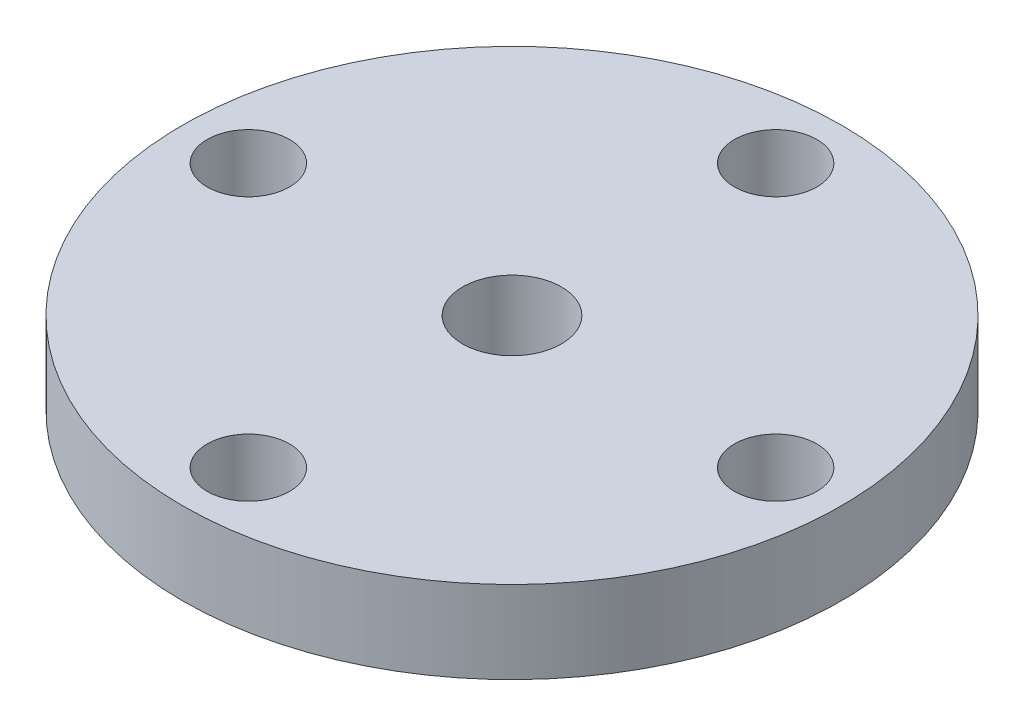
SolidWorks part; units mm, degrees
ref_plane "Front Plane" through (0, 0, 0) normal (0, 0, 1) x (1, 0, 0)
ref_plane "Top Plane" through (0, 0, 0) normal (0, 1, 0) x (1, 0, 0)
ref_plane "Right Plane" through (0, 0, 0) normal (1, 0, 0) x (0, 0, -1)
sketch "Sketch1" plane through (0, 0, 0) normal (0, 1, 0) x (1, 0, 0)
  line L0 (0, 24.1217) -> (0, -25.5168) construction
  line L1 (-33.1168, 0) -> (38.4772, 0) construction
  circle A0 centre (0, 0) radius 10
  circle A1 centre (0, 0) radius 1.5
  circle A2 centre (0, 8) radius 1.25
  circle A3 centre (0, 0) radius 10
  circle A4 centre (8, 0) radius 1.25
  circle A5 centre (0, 0) radius 10
  circle A6 centre (0, -8) radius 1.25
  circle A7 centre (0, 0) radius 10
  circle A8 centre (-8, 0) radius 1.25
  point P22 (0, 0)
  dimension "D1" = 20
  dimension "D2" = 3
  dimension "D3" = 2.5
  dimension "D5" = 8
  dimension "D4" = 4
extrude "Boss-Extrude1" add sketch "Sketch1" along normal blind 2.5 contours A0 A8 A6 A4 A2 A1
cosmetic thread "Cosmetic Thread1" parameters "D1"=2.4999, "D2"=3
cosmetic thread "Cosmetic Thread2" parameters "D1"=2.4999, "D2"=3
cosmetic thread "Cosmetic Thread3" parameters "D1"=2.4999, "D2"=3
cosmetic thread "Cosmetic Thread4" parameters "D1"=2.4999, "D2"=3
